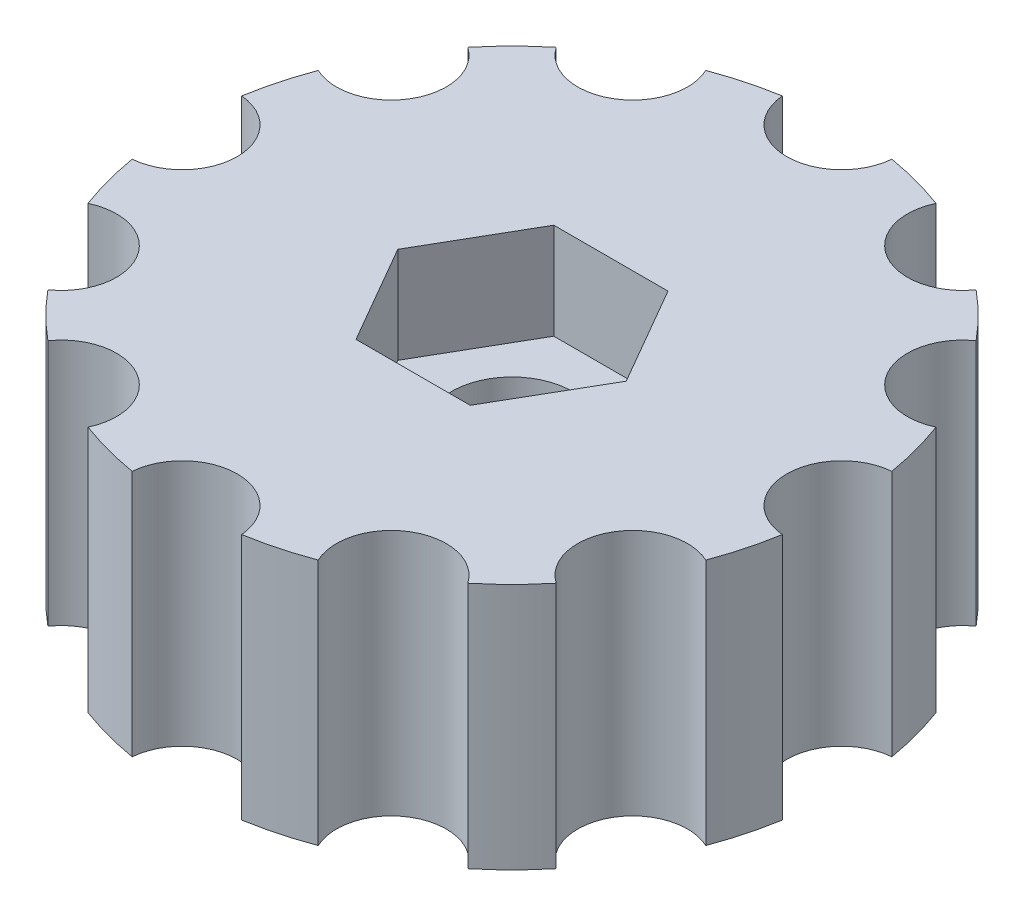
SolidWorks part; units mm, degrees
ref_plane "Front Plane" through (0, 0, 0) normal (0, 0, 1) x (1, 0, 0)
ref_plane "Top Plane" through (0, 0, 0) normal (0, 1, 0) x (1, 0, 0)
ref_plane "Right Plane" through (0, 0, 0) normal (1, 0, 0) x (0, 0, -1)
sketch "Croquis_perilla" plane through (0, 0, 0) normal (0, 1, 0) x (1, 0, 0)
  circle A0 centre (0, 0) radius 12
  dimension "D1" = 24
extrude "Cuerpo" add sketch "Croquis_perilla" along normal blind 9
sketch "Croquis_moleteado" plane through (0, 0, 0) normal (0, 1, 0) x (1, 0, 0)
  circle A0 centre (12, 0) radius 2
  circle A1 centre (10.3923, 6) radius 2
  circle A2 centre (6, 10.3923) radius 2
  circle A3 centre (0, 12) radius 2
  circle A4 centre (-6, 10.3923) radius 2
  circle A5 centre (-10.3923, 6) radius 2
  circle A6 centre (-12, 0) radius 2
  circle A7 centre (-10.3923, -6) radius 2
  circle A8 centre (-6, -10.3923) radius 2
  circle A9 centre (0, -12) radius 2
  circle A10 centre (6, -10.3923) radius 2
  circle A11 centre (10.3923, -6) radius 2
  dimension "D1" = 4
extrude "Moleteado" cut sketch "Croquis_moleteado" along normal through all and the other way through all
sketch "Croquis_arandela" plane through (0, 0, 0) normal (0, 1, 0) x (1, 0, 0)
  circle A0 centre (0, 0) radius 5.5
  dimension "D1" = 11
extrude "Arandela" add sketch "Croquis_arandela" against normal blind 2
sketch "Croquis_paso" plane through (0, 0, 0) normal (0, 1, 0) x (1, 0, 0)
  circle A0 centre (0, 0) radius 2.2
  dimension "D1" = 4.4
extrude "Paso_M4" cut sketch "Croquis_paso" along normal through all and the other way through all
ref_plane "Plano_Top Plane_+9" through (0, 9, 0) normal (0, 1, 0) x (1, 0, 0)
sketch "Croquis_cabeza" plane through (0, 9, 0) normal (0, 1, 0) x (1, 0, 0)
  line L0 (4.1569, 0) -> (2.0785, 3.6)
  line L1 (2.0785, 3.6) -> (-2.0785, 3.6)
  line L2 (-2.0785, 3.6) -> (-4.1569, 0)
  line L3 (-4.1569, 0) -> (-2.0785, -3.6)
  line L4 (-2.0785, -3.6) -> (2.0785, -3.6)
  line L5 (2.0785, -3.6) -> (4.1569, 0)
extrude "Cabeza_M4" cut sketch "Croquis_cabeza" against normal blind 3.5
